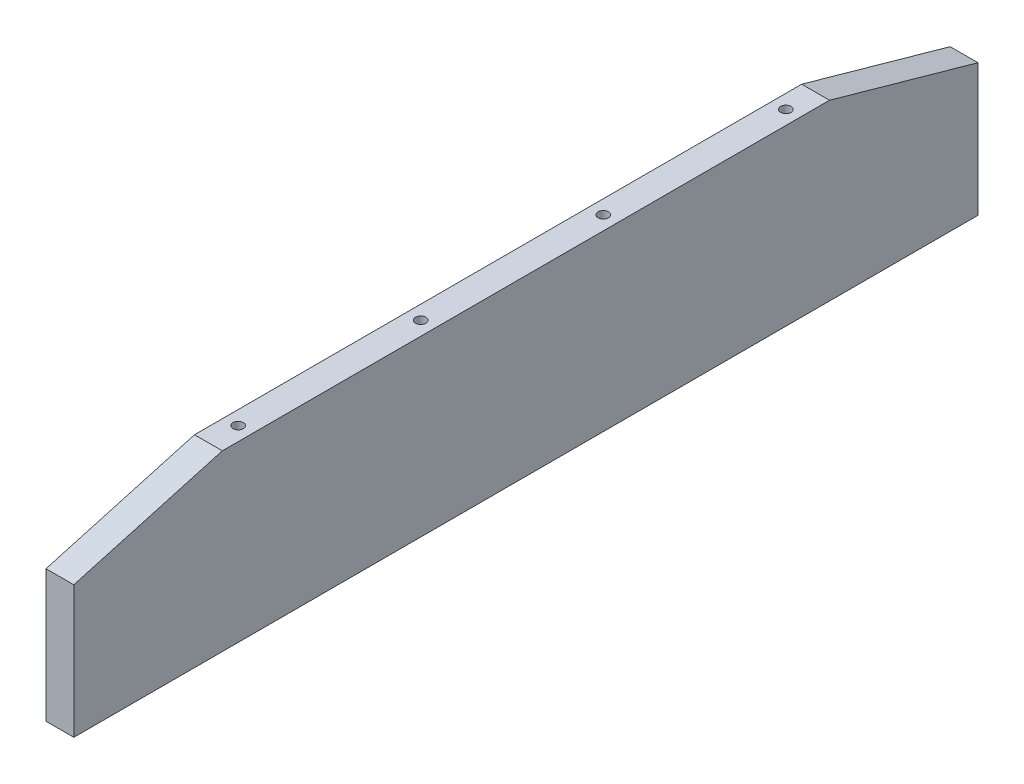
SolidWorks part; units mm, degrees
ref_plane "Front Plane" through (0, 0, 0) normal (0, 0, 1) x (1, 0, 0)
ref_plane "Top Plane" through (0, 0, 0) normal (0, 1, 0) x (1, 0, 0)
ref_plane "Right Plane" through (0, 0, 0) normal (1, 0, 0) x (0, 0, -1)
sketch "Sketch1" plane through (0, 0, 0) normal (1, 0, 0) x (0, 0, -1)
  line L0 (-25, 0) -> (235, 0)
  line L1 (235, 0) -> (235, 37.9953)
  line L2 (235, 37.9953) -> (192.3016, 50)
  line L3 (192.3016, 50) -> (17.6984, 50)
  line L4 (17.6984, 50) -> (-25, 37.9953)
  line L5 (-25, 37.9953) -> (-25, 0)
  line L7 (210, 50) -> (0, 50) construction
  line L8 (210, 50) -> (210, 0) construction
  line L9 (210, 0) -> (0, 0) construction
  line L10 (0, 50) -> (0, 0) construction
extrude "Boss-Extrude1" add sketch "Sketch1" along normal blind 8
sketch "Sketch6" plane through (0, 0, 0) normal (0, -1, 0) x (1, 0, 0)
  line L0 (4, 25) -> (4, -235) construction
  line L1 (8, 25) -> (0, 25) construction
  line L2 (8, -235) -> (0, -235) construction
  circle A0 centre (4, -26.25) radius 1.5
  circle A1 centre (4, -78.75) radius 1.5
  circle A2 centre (4, -131.25) radius 1.5
  circle A3 centre (4, -183.75) radius 1.5
extrude "Cut-Extrude2" cut sketch "Sketch6" against normal blind 50
